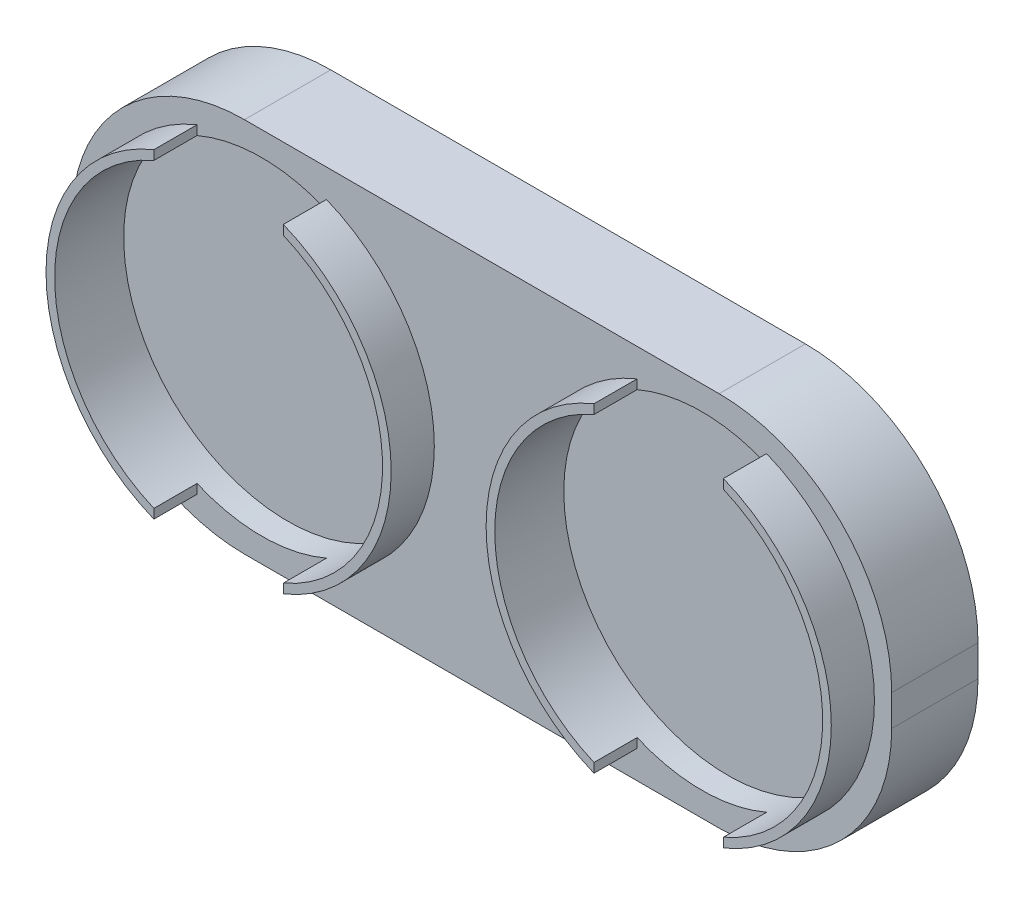
SolidWorks part; units mm, degrees
ref_plane "Front Plane" through (0, 0, 0) normal (1, 0, 0) x (0, 1, 0)
ref_plane "Top Plane" through (0, 0, 0) normal (0, 0, 1) x (0, 1, 0)
ref_plane "Right Plane" through (0, 0, 0) normal (0, 1, 0) x (-1, 0, 0)
sketch "Sketch1" plane through (0, 0, 0) normal (0, 0, 1) x (0, 1, 0)
  line L1 (-21.8, -47.5) -> (21.8, -47.5)
  line L2 (-21.8, -47.5) -> (-21.8, 47.5)
  line L3 (-21.8, 47.5) -> (21.8, 47.5)
  line L4 (21.8, -47.5) -> (21.8, 47.5)
  line L5 (-21.8, -47.5) -> (21.8, 47.5) construction
  line L6 (-21.8, 47.5) -> (21.8, -47.5) construction
  point P0 (0, 0)
extrude "Boss-Extrude1" add sketch "Sketch1" along normal blind 10
sketch "Sketch2" plane through (0, 0, 0) normal (0, 0, -1) x (1, 0, 0)
  line L0 (0, 21.8) -> (0, -21.8) construction
  line L1 (-47.5, 21.8) -> (47.5, 21.8) construction
  line L2 (47.5, -21.8) -> (-47.5, -21.8) construction
  line L3 (-47.5, 0) -> (47.5, 0) construction
  line L4 (-47.5, -21.8) -> (-47.5, 21.8) construction
  line L5 (47.5, 21.8) -> (47.5, -21.8) construction
  line L6 (0, 8.55) -> (0, 0)
  circle A0 centre (0, 12.45) radius 3.9
  circle A1 centre (0, -12.45) radius 3.9
  dimension "D1" = 7.8
extrude "Boss-Extrude2" add sketch "Sketch2" along normal blind 4 contours A0 | A1
sketch "Sketch5" plane through (0, 0, 10) normal (0, 0, 1) x (1, 0, 0)
  line L0 (-47.5, 0) -> (47.5, 0) construction
  line L1 (-47.5, 21.8) -> (-47.5, -21.8) construction
  line L2 (47.5, -21.8) -> (47.5, 21.8) construction
  line L3 (0, 21.8) -> (0, -21.8) construction
  line L4 (47.5, 21.8) -> (-47.5, 21.8) construction
  line L5 (-47.5, -21.8) -> (47.5, -21.8) construction
  line L6 (-47.5, 0) -> (-45.5, 0)
  circle A0 centre (-25.5, 0) radius 19
  circle A1 centre (-25.5, 0) radius 20
  circle A2 centre (25.5, 0) radius 20
  circle A3 centre (25.5, 0) radius 19
  dimension "D1" = 38
  dimension "D2" = 1
extrude "Boss-Extrude4" add sketch "Sketch5" along normal blind 5 contours A1 A0 | A2 A3
sketch "Sketch6" plane through (0, 0, 15) normal (0, 0, 1) x (1, 0, 0)
  line L1 (-33, -21.8) -> (-18, -21.8)
  line L2 (-33, -21.8) -> (-33, 21.8)
  line L3 (-33, 21.8) -> (-18, 21.8)
  line L4 (-18, -21.8) -> (-18, 21.8)
  line L5 (-33, -21.8) -> (-18, 21.8) construction
  line L6 (-33, 21.8) -> (-18, -21.8) construction
  line L7 (47.5, 21.8) -> (-47.5, 21.8) construction
  line L8 (0, 21.8) -> (0, -21.8) construction
  line L9 (-47.5, -21.8) -> (47.5, -21.8) construction
  line L10 (33, 21.8) -> (18, -21.8) construction
  line L11 (33, -21.8) -> (18, 21.8) construction
  line L12 (18, -21.8) -> (18, 21.8)
  line L13 (33, 21.8) -> (18, 21.8)
  line L14 (33, -21.8) -> (33, 21.8)
  line L15 (33, -21.8) -> (18, -21.8)
  point P0 (-25.5, 0)
  point P17 (25.5, 0)
  dimension "D1" = 43.6
  dimension "D2" = 15
extrude "Cut-Extrude1" cut sketch "Sketch6" against normal up to surface (5 mm away) up to face at (45.5, 0, 10)
fillet "Fillet1" radius 20 4 edges at (-47.5, 21.8, 5) (-47.5, -21.8, 5) (47.5, -21.8, 5) (47.5, 21.8, 5)
sketch "Sketch7" plane through (0, 0, 10) normal (0, 0, 1) x (1, 0, 0)
  line L0 (0, 21.8) -> (0, -21.8) construction
  line L1 (27.5, 21.8) -> (-27.5, 21.8) construction
  line L2 (-27.5, -21.8) -> (27.5, -21.8) construction
  circle A0 centre (-25.5, 0) radius 19
  circle A1 centre (25.5, 0) radius 19
extrude "Cut-Extrude2" cut sketch "Sketch7" against normal blind 3
pattern_linear "LPattern1" count 2 spacing 24.87 along (-1, 0, 0) count 2 spacing 24.87 along (1, 0, 0) of "Boss-Extrude2"
fillet "Fillet3" radius 0.4 6 edges at (20.97, 12.45, -4) (20.97, -12.45, -4) (-28.77, 12.45, -4) (-28.77, -12.45, -4) (-3.9, 12.45, -4) (-3.9, -12.45, -4)
